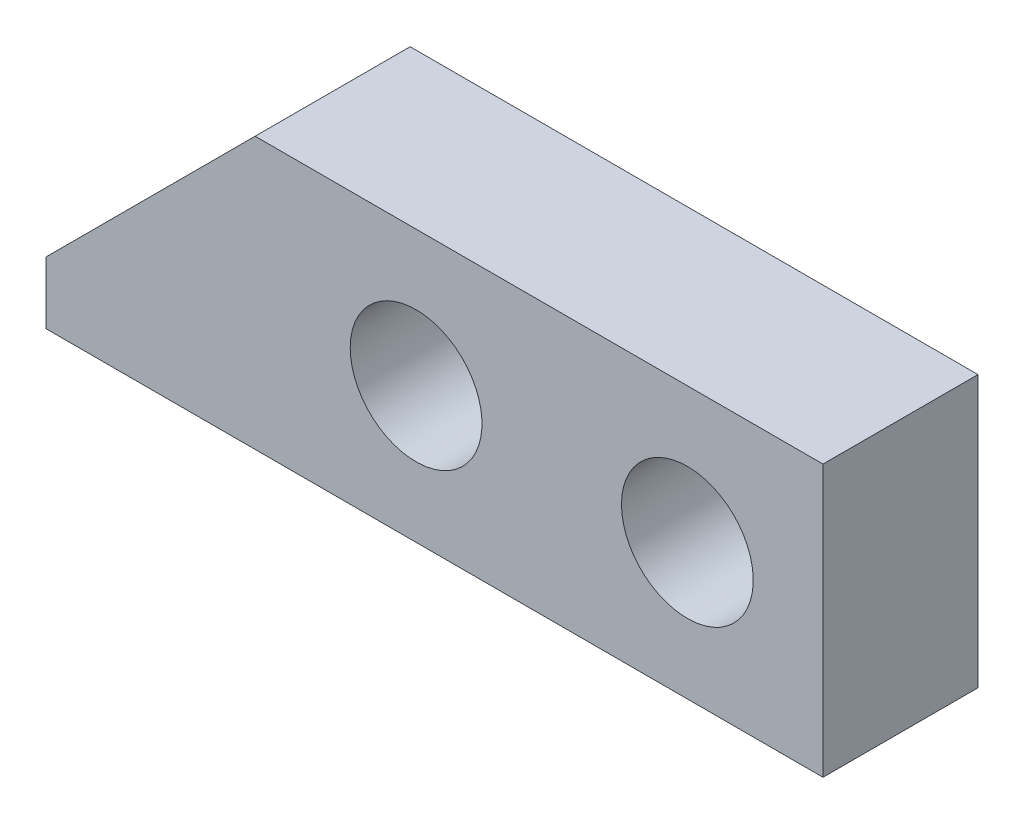
SolidWorks part; units mm, degrees
material "POLYURETHANE (11671)"
ref_plane "Front Plane" through (0, 0, 0) normal (0, 0, 1) x (1, 0, 0)
ref_plane "Top Plane" through (0, 0, 0) normal (0, 1, 0) x (1, 0, 0)
ref_plane "Right Plane" through (0, 0, 0) normal (1, 0, 0) x (0, 0, -1)
sketch "Sketch1" plane through (0, 0, 0) normal (0, 0, 1) x (1, 0, 0)
  line L1 (55, 0) -> (-55, 0) construction
  line L2 (5.3964, 7) -> (20.05, 7)
  line L3 (20.05, 7) -> (20.05, 0)
  line L4 (20.05, 0) -> (0, 0)
  line L5 (0, -55) -> (0, 55) construction
  line L6 (0, 1.6036) -> (0, 0)
  line L7 (5.3964, 7) -> (0, 1.6036)
  line L8 (0, 3) -> (0, 1.6036) construction
  line L9 (5, 7) -> (5.3964, 7) construction
  arc A1 (5, 7) -> (0, 3) centre (5, 1.875) ccw construction
  point P17 (1.7984, 5.877)
  dimension "D1" = 7
  dimension "D3" = 15.05
  dimension "D4" = 5
  dimension "D2" = 3
  dimension "D6" = 45
  dimension "D5" = 1.75
extrude "Boss-Extrude1" add sketch "Sketch1" along normal blind 4
hole_wizard "CSK for M3 Countersunk Flat Head Screw1" positions "Sketch2" profile "Sketch3" countersink size "M3" standard "ISO" end condition through all
sketch "Sketch2" plane through (0, 0, 0) normal (0, 0, 1) x (1, 0, 0)
  line L0 (20.05, 0) -> (20.05, 7) construction
  line L1 (55, 0) -> (-55, 0) construction
  point P0 (16.55, 3.5)
  point P2 (9.55, 3.5)
  dimension "D1" = 7
  dimension "D2" = 3.5
  dimension "D3" = 3.5
sketch "Sketch3" plane through (16.55, 3.5, 0) normal (1, 0, 0) x (0, 1, 0)
  line L0 (0, 0) -> (0, 4)
  line L1 (0, 4) -> (1.7, 4)
  line L2 (1.7, 4) -> (1.7, 1.45)
  line L3 (1.7, 1.45) -> (3.15, 0)
  line L5 (3.15, 0) -> (0, 0)
  line L6 (-1.7, 1.45) -> (-3.15, 0) construction
  line L11 (0, -6.35) -> (0, 107.95) construction
  dimension "Thru Hole Dia." = 3.4
  dimension "Thru Hole Depth" = 4
  dimension "Near C'Sink Dia." = 6.3
  dimension "Near C'Sink Angle" = 90
hole_wizard "Tap Drill for M2 Tap1" positions "Sketch4" profile "Sketch5" hole size "M2" standard "DIN" end condition through all
sketch "Sketch4" plane through (-0.8018, 0.8018, 0) normal (-0.7071, 0.7071, 0) x (0, 0, 1)
  line L0 (4, 8.7655) -> (0, 8.7655) construction
  line L1 (0, 8.7655) -> (0, 1.1339) construction
  point P0 (2, 4.9497)
  point P7 (2, 8.7655)
  point P10 (0, 4.9497)
sketch "Sketch5" plane through (2.6982, 4.3018, 2) normal (0, 0, 1) x (-0.7071, -0.7071, 0)
  line L0 (0, 0) -> (0, 15.3114)
  line L1 (0, 15.3114) -> (0.95, 15.3114)
  line L2 (0.95, 15.3114) -> (0.95, 0)
  line L5 (0.95, 0) -> (0, 0)
  line L11 (0, -6.35) -> (0, 107.95) construction
  dimension "Thru Hole Dia." = 1.9
  dimension "Thru Hole Depth" = 15.3114
equation "\"D3@Sketch1\"=13.750mm+1.3"
